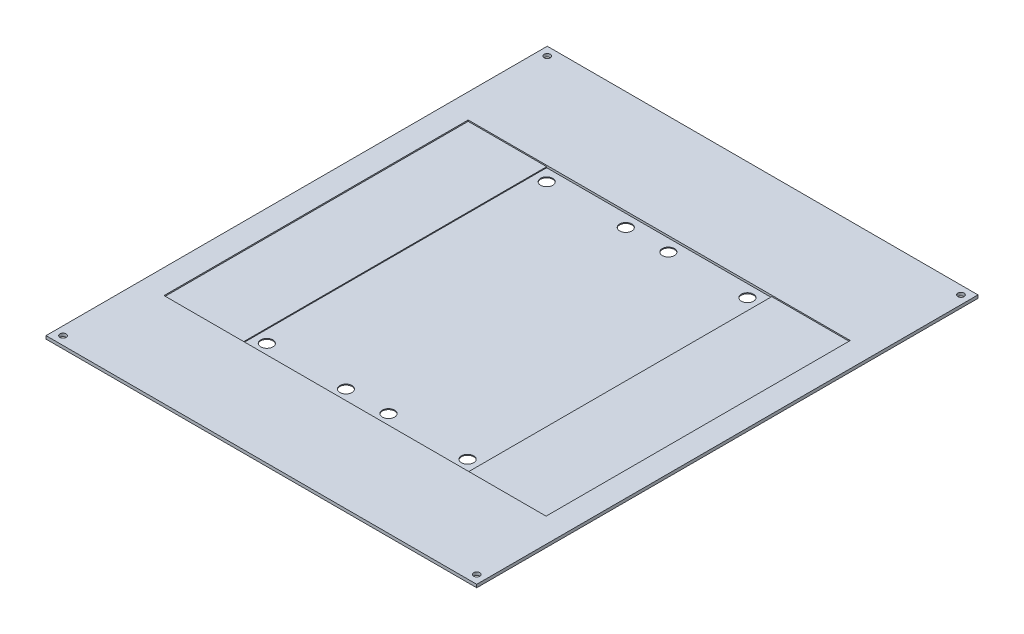
SolidWorks part; units mm, degrees
ref_plane "Front Plane" through (0, 0, 0) normal (0, 0, 1) x (1, 0, 0)
ref_plane "Top Plane" through (0, 0, 0) normal (0, 1, 0) x (1, 0, 0)
ref_plane "Right Plane" through (0, 0, 0) normal (1, 0, 0) x (0, 0, -1)
sketch "Sketch1" plane through (0, 0, 0) normal (0, 1, 0) x (1, 0, 0)
  line L1 (0, 0) -> (708, 0)
  line L2 (0, 0) -> (0, 824)
  line L3 (0, 824) -> (708, 824)
  line L4 (708, 0) -> (708, 824)
  dimension "D1" = 824
  dimension "D2" = 708
extrude "Boss-Extrude1" add sketch "Sketch1" along normal blind 5
sketch "Sketch2" plane through (0, 5, 0) normal (0, 1, 0) x (1, 0, 0)
  line L0 (708, 824) -> (0, 824) construction
  line L1 (169, 654) -> (539, 654)
  line L2 (169, 654) -> (169, 154)
  line L3 (169, 154) -> (539, 154)
  line L4 (539, 654) -> (539, 154)
  line L5 (0, 824) -> (0, 0) construction
  point P6 (354, 654)
  dimension "D1" = 170
  dimension "D2" = 370
  dimension "D3" = 500
  dimension "D4" = 354
extrude "Cut-Extrude1" cut sketch "Sketch2" against normal blind 3.5
sketch "Sketch3" plane through (0, 5, 0) normal (0, 1, 0) x (1, 0, 0)
  line L0 (539, 654) -> (169, 654) construction
  line L1 (40, 654) -> (668, 654)
  line L2 (40, 654) -> (40, 154)
  line L3 (40, 154) -> (668, 154)
  line L4 (668, 654) -> (668, 154)
  line L5 (0, 824) -> (0, 0) construction
  line L6 (708, 0) -> (708, 824) construction
  dimension "D1" = 0
  dimension "D2" = 0
  dimension "D3" = 40
  dimension "D4" = 40
extrude "Cut-Extrude2" cut sketch "Sketch3" against normal blind 2
sketch "Sketch4" plane through (0, 1.5, 0) normal (0, 1, 0) x (1, 0, 0)
  line L0 (169, 154) -> (169, 654) construction
  line L1 (668, 654) -> (40, 654) construction
  line L2 (539, 654) -> (169, 654) construction
  line L3 (539, 154) -> (539, 654) construction
  line L4 (169, 404) -> (539, 404) construction
  line L6 (169, 654) -> (169, 154) construction
  circle A8 centre (189, 634) radius 10
  circle A9 centre (319, 634) radius 10
  circle A22 centre (389, 634) radius 10
  circle A23 centre (519, 634) radius 10
  circle A28 centre (519, 174) radius 10
  circle A29 centre (389, 174) radius 10
  circle A30 centre (319, 174) radius 10
  circle A31 centre (189, 174) radius 10
  dimension "D1" = 20
  dimension "D2" = 20
  dimension "D3" = 20
  dimension "D4" = 20
  dimension "D5" = 20
  dimension "D6" = 20
  dimension "D7" = 20
  dimension "D8" = 130
  dimension "D9" = 70
ref_plane "Plane2" through (0, 0, -404) normal (0, 0, -1) x (-1, 0, 0)
sketch "Sketch6" plane through (0, 5, 0) normal (0, 1, 0) x (1, 0, 0)
  line L1 (169, 154) -> (539, 154)
  line L2 (169, 154) -> (169, 654)
  line L3 (169, 654) -> (539, 654)
  line L4 (539, 154) -> (539, 654)
  line L5 (168.8, 654.2) -> (539.2, 654.2)
  line L6 (168.8, 654.2) -> (168.8, 153.8)
  line L7 (168.8, 153.8) -> (539.2, 153.8)
  line L8 (539.2, 654.2) -> (539.2, 153.8)
  dimension "D1" = 0.2
  dimension "D2" = 0.2
  dimension "D3" = 0.2
  dimension "D4" = 0.2
sketch "Sketch11" plane through (0, 5, 0) normal (0, 1, 0) x (1, 0, 0)
  line L0 (0, 0) -> (708, 0) construction
  line L1 (0, 824) -> (0, 0) construction
  circle A0 centre (14, 14) radius 5.1
  dimension "D1" = 10.2
  dimension "D2" = 14
  dimension "D3" = 14
extrude "Cut-Extrude7" cut sketch "Sketch11" against normal blind 23.2
ref_plane "Plane3" through (354, 0, 0) normal (1, 0, 0) x (0, 0, -1)
ref_plane "Plane4" through (0, 0, -412) normal (0, 0, 1) x (1, 0, 0)
mirror "Mirror4" about plane through (354, 0, 0) normal (1, 0, 0) of "Cut-Extrude7" second plane through (0, 0, -412) second plane normal (0, 0, 1)
extrude "Cut-Extrude8" cut sketch "Sketch4" against normal through all
